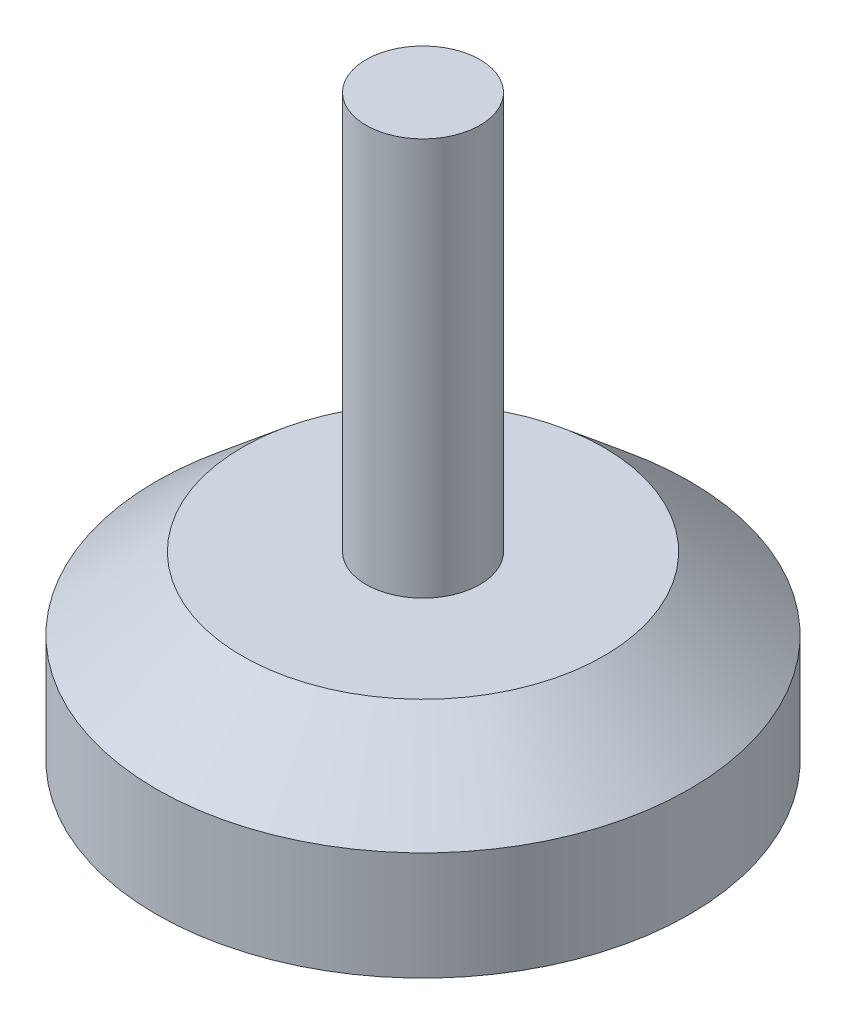
SolidWorks part; units mm, degrees
ref_plane "Plano frontal" through (0, 0, 0) normal (0, 0, 1) x (1, 0, 0)
ref_plane "Plano superior" through (0, 0, 0) normal (0, 1, 0) x (1, 0, 0)
ref_plane "Plano direito" through (0, 0, 0) normal (1, 0, 0) x (0, 0, -1)
sketch "Esboço1" plane through (0, 0, 0) normal (0, 0, 1) x (1, 0, 0)
  line L0 (0, 0) -> (0, 32)
  line L1 (0, 0) -> (-14.75, 0)
  line L2 (-14.75, 0) -> (-14.75, 6)
  line L3 (0, 32) -> (-3.15, 32)
  line L6 (-14.75, 6) -> (-10, 10)
  line L7 (-10, 10) -> (-3.15, 10)
  line L8 (-3.15, 10) -> (-3.15, 32)
  point P1 (-6.575, 10)
  dimension "D1" = 22
  dimension "D2" = 3.15
  dimension "D3" = 10
  dimension "D4" = 14.75
  dimension "D5" = 6
  dimension "D7" = 10
revolve "Revolução1" add sketch "Esboço1" angle 360 about L0
